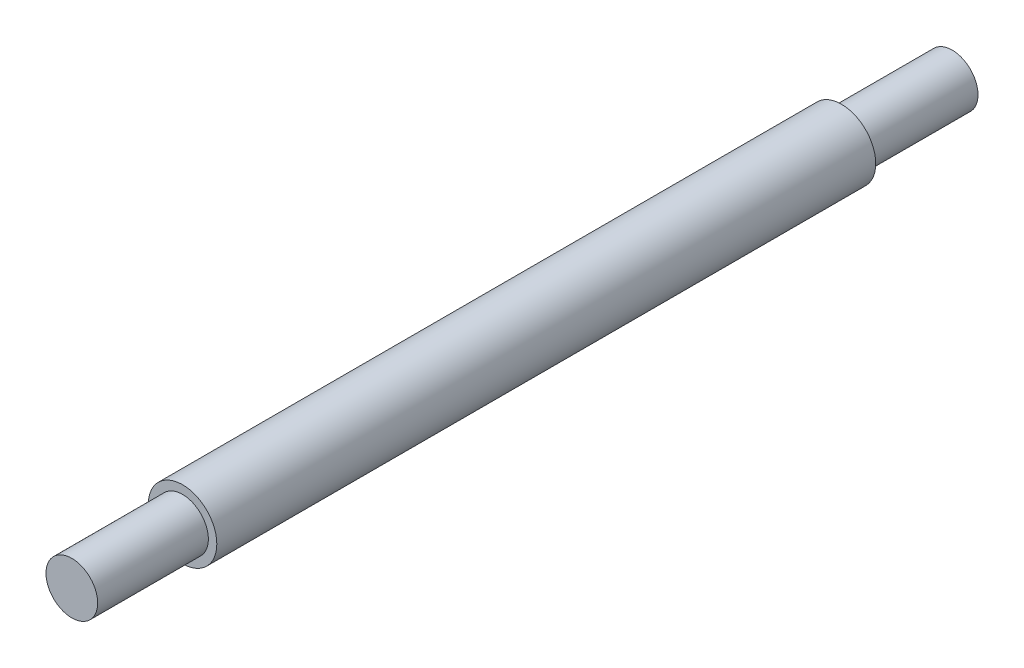
SolidWorks part; units mm, degrees
ref_plane "前视基准面" through (0, 0, 0) normal (0, 0, 1) x (1, 0, 0)
ref_plane "上视基准面" through (0, 0, 0) normal (0, 1, 0) x (1, 0, 0)
ref_plane "右视基准面" through (0, 0, 0) normal (1, 0, 0) x (0, 0, -1)
other "Configuration Table"
sketch "草图1" plane through (0, 0, 0) normal (0, 0, 1) x (1, 0, 0)
  circle A0 centre (0, 0) radius 6.5
  dimension "D1" = 13
extrude "凸台-拉伸1" add sketch "草图1" along normal blind 125
sketch "草图2" plane through (0, 0, 125) normal (0, 0, 1) x (1, 0, 0)
  circle A0 centre (0, 0) radius 4.9
  dimension "D1" = 9.8
extrude "凸台-拉伸2" add sketch "草图2" along normal blind 21
sketch "草图3" plane through (0, 0, 0) normal (0, 0, -1) x (-1, 0, 0)
  circle A0 centre (0, 0) radius 4.9
  dimension "D1" = 9.8
extrude "凸台-拉伸3" add sketch "草图3" along normal blind 21
